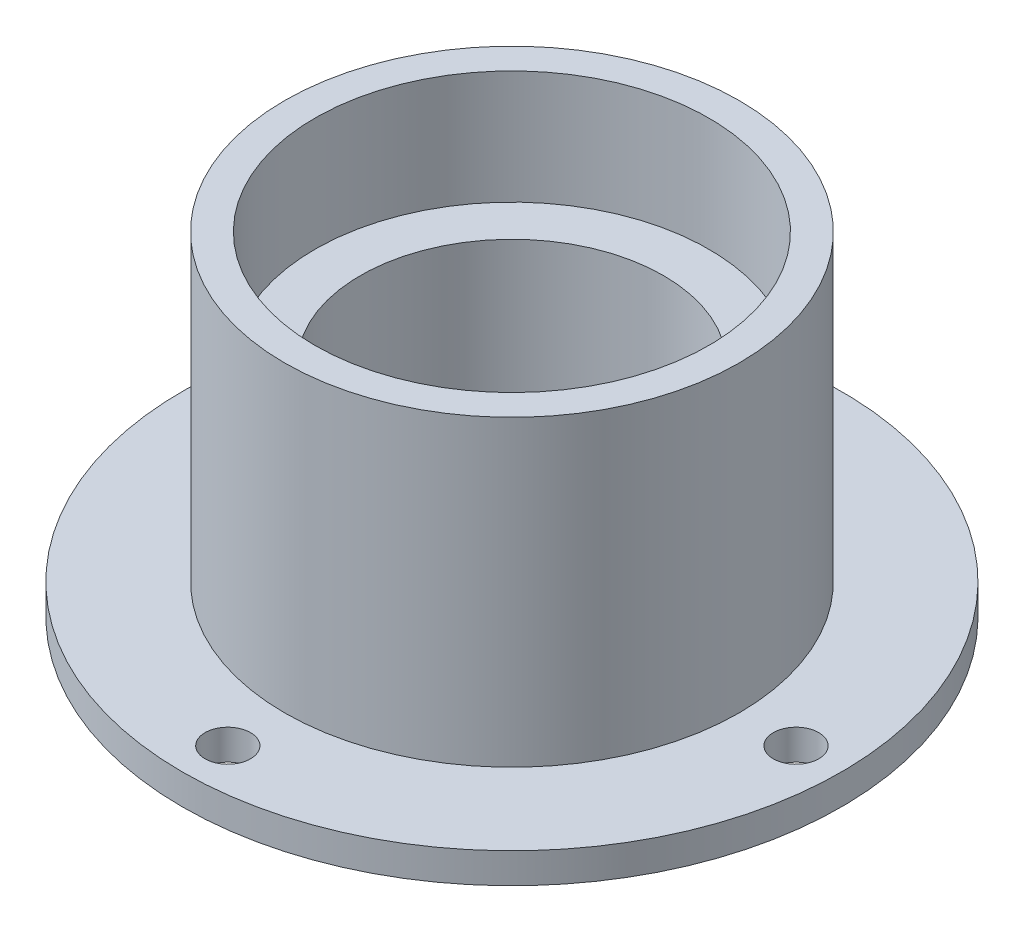
SolidWorks part; units mm, degrees
ref_plane "Alzado" through (0, 0, 0) normal (0, 0, 1) x (1, 0, 0)
ref_plane "Planta" through (0, 0, 0) normal (0, 1, 0) x (1, 0, 0)
ref_plane "Vista lateral" through (0, 0, 0) normal (1, 0, 0) x (0, 0, -1)
sketch "Croquis1" plane through (0, 0, 0) normal (0, 1, 0) x (1, 0, 0)
  circle A0 centre (0, 0) radius 30
  circle A1 centre (0, 0) radius 43.5
  dimension "D1" = 60
  dimension "D2" = 87
extrude "Saliente-Extruir1" add sketch "Croquis1" along normal blind 4
sketch "Croquis2" plane through (0, 0, 0) normal (0, 1, 0) x (1, 0, 0)
  circle A0 centre (0, 0) radius 20
  circle A1 centre (0, 0) radius 30
  dimension "D1" = 40
  dimension "D2" = 60
extrude "Saliente-Extruir2" add sketch "Croquis2" along normal blind 44
sketch "Croquis3" plane through (0, 0, 0) normal (0, 1, 0) x (1, 0, 0)
  circle A0 centre (0, 0) radius 20
  circle A1 centre (0, 0) radius 30
  dimension "D1" = 40
  dimension "D2" = 60
extrude "Cortar-Extruir1" cut sketch "Croquis3" along normal blind 2
sketch "Croquis4" plane through (0, 44, 0) normal (0, 1, 0) x (1, 0, 0)
  circle A0 centre (0, 0) radius 26
  dimension "D1" = 52
extrude "Cortar-Extruir2" cut sketch "Croquis4" against normal blind 15
sketch "Croquis5" plane through (0, 0, 0) normal (0, 1, 0) x (1, 0, 0)
  circle A0 centre (0, 0) radius 37.5
  circle A1 centre (0, -37.5) radius 3
  circle A2 centre (-37.5, 0) radius 3
  circle A3 centre (0, 37.5) radius 3
  circle A4 centre (37.5, 0) radius 3
  point P14 (0, 0)
  dimension "D1" = 75
  dimension "D2" = 6
  dimension "D3" = 4
extrude "Cortar-Extruir3" cut sketch "Croquis5" along normal up to surface (4 mm away) contours A0 A1 | A0 A1 | A0 A4 | A0 A4 | A0 A3 | A0 A3 | A0 A2 | A0 A2
